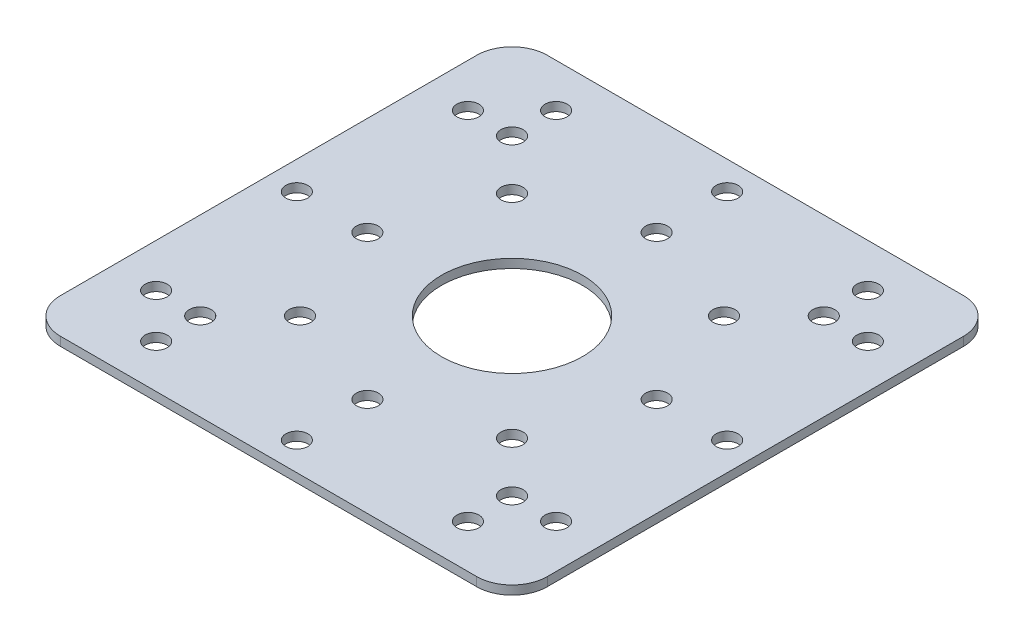
SolidWorks part; units mm, degrees
ref_plane "Front Plane" through (0, 0, 0) normal (0, 0, 1) x (1, 0, 0)
ref_plane "Top Plane" through (0, 0, 0) normal (0, 1, 0) x (1, 0, 0)
ref_plane "Right Plane" through (0, 0, 0) normal (1, 0, 0) x (0, 0, -1)
sketch "Sketch1" plane through (0, 0, 0) normal (0, 1, 0) x (1, 0, 0)
  line L1 (29.972, -35.052) -> (-29.972, -35.052)
  line L2 (35.052, -29.972) -> (35.052, 29.972)
  line L3 (29.972, 35.052) -> (-29.972, 35.052)
  line L4 (-35.052, -29.972) -> (-35.052, 29.972)
  line L5 (35.052, -35.052) -> (-35.052, 35.052) construction
  line L6 (35.052, 35.052) -> (-35.052, -35.052) construction
  arc A0 (-35.052, -29.972) -> (-29.972, -35.052) centre (-29.972, -29.972) ccw
  arc A1 (29.972, -35.052) -> (35.052, -29.972) centre (29.972, -29.972) ccw
  arc A2 (35.052, 29.972) -> (29.972, 35.052) centre (29.972, 29.972) ccw
  arc A3 (-29.972, 35.052) -> (-35.052, 29.972) centre (-29.972, 29.972) ccw
  point P0 (0, 0)
  dimension "D3" = 5.08
  dimension "D1" = 70.104
  dimension "D2" = 70.104
extrude "Boss-Extrude1" add sketch "Sketch1" along normal blind 1.27
sketch "Sketch2" plane through (0, 1.27, 0) normal (0, 1, 0) x (1, 0, 0)
  circle A0 centre (0, 0) radius 10.16
  circle A1 centre (20.8338, 0) radius 1.5875
  circle A2 centre (30.988, 0) radius 1.5875
  circle A3 centre (-20.8338, 0) radius 1.5875
  circle A4 centre (-30.988, 0) radius 1.5875
  circle A5 centre (0, -20.828) radius 1.5875
  circle A6 centre (0, 30.988) radius 1.5875
  circle A7 centre (0, 20.828) radius 1.5875
  circle A9 centre (-15.2664, -15.2664) radius 1.5875
  circle A10 centre (-22.4506, -22.4506) radius 1.5875
  circle A11 centre (-28.8006, -22.4506) radius 1.5875
  circle A12 centre (-22.4506, -28.8006) radius 1.5875
  circle A13 centre (28.8006, -22.4506) radius 1.5875
  circle A14 centre (22.4506, -28.8006) radius 1.5875
  circle A15 centre (22.4506, -22.4506) radius 1.5875
  circle A16 centre (15.2664, -15.2664) radius 1.5875
  circle A17 centre (28.8006, 22.4506) radius 1.5875
  circle A18 centre (22.4506, 28.8006) radius 1.5875
  circle A19 centre (22.4506, 22.4506) radius 1.5875
  circle A20 centre (15.2664, 15.2664) radius 1.5875
  circle A21 centre (-22.4506, 28.8006) radius 1.5875
  circle A22 centre (-28.8006, 22.4506) radius 1.5875
  circle A23 centre (-15.2664, 15.2664) radius 1.5875
  circle A24 centre (-22.4506, 22.4506) radius 1.5875
  circle A26 centre (0, -30.988) radius 1.5875
  dimension "D1" = 20.32
  dimension "D3" = 3.175
  dimension "D4" = 3.175
  dimension "D5" = 3.175
  dimension "D6" = 3.175
  dimension "D7" = 3.175
  dimension "D8" = 3.175
  dimension "D9" = 3.175
  dimension "D10" = 3.175
  dimension "D11" = 3.175
  dimension "D12" = 3.175
  dimension "D13" = 3.175
  dimension "D14" = 3.175
  dimension "D15" = 3.175
  dimension "D16" = 3.175
  dimension "D17" = 3.175
  dimension "D18" = 3.175
  dimension "D19" = 3.175
  dimension "D20" = 3.175
  dimension "D21" = 3.175
  dimension "D22" = 3.175
  dimension "D23" = 3.175
  dimension "D24" = 3.175
  dimension "D25" = 3.175
  dimension "D26" = 3.175
extrude "Cut-Extrude1" cut sketch "Sketch2" against normal through all
equation "\"HOLE SIZE\"= .125"
equation "\"DENSITY\"= .1"
